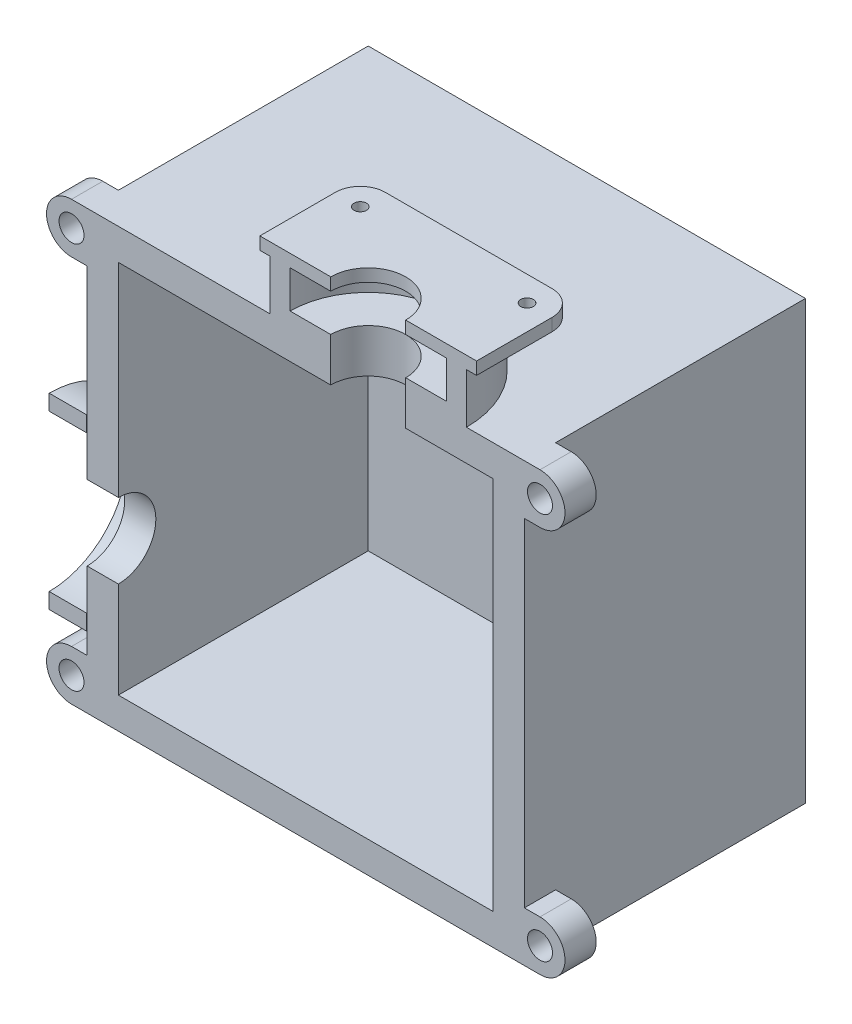
SolidWorks part; units mm, degrees
ref_plane "前视基准面" through (0, 0, 0) normal (0, 0, 1) x (1, 0, 0)
ref_plane "上视基准面" through (0, 0, 0) normal (0, 1, 0) x (1, 0, 0)
ref_plane "右视基准面" through (0, 0, 0) normal (1, 0, 0) x (0, 0, -1)
sketch "草图1" plane through (0, 0, 0) normal (0, 0, 1) x (1, 0, 0)
  line L1 (-45, -45) -> (45, -45)
  line L2 (-45, -45) -> (-45, 45)
  line L3 (-45, 45) -> (45, 45)
  line L4 (45, -45) -> (45, 45)
  line L5 (-45, -45) -> (45, 45) construction
  line L6 (-45, 45) -> (45, -45) construction
  point P0 (0, 0)
  dimension "D1" = 90
extrude "凸台-拉伸2" add sketch "草图1" along normal blind 45
sketch "草图2" plane through (0, 0, 45) normal (0, 0, 1) x (1, 0, 0)
  line L1 (-40, -40) -> (40, -40)
  line L2 (-40, -40) -> (-40, 40)
  line L3 (-40, 40) -> (40, 40)
  line L4 (40, -40) -> (40, 40)
  line L5 (-40, -40) -> (40, 40) construction
  line L6 (-40, 40) -> (40, -40) construction
  point P0 (0, 0)
extrude "切除-拉伸1" cut sketch "草图2" against normal blind 40
sketch "草图3" plane through (0, 45, 0) normal (0, 1, 0) x (1, 0, 0)
  line L0 (45, -45) -> (-45, -45) construction
  line L1 (-15.725, -45) -> (15.725, -45)
  arc A0 (15.725, -45) -> (-15.725, -45) centre (0, -45) ccw
  dimension "D1" = 31.45
extrude "凸台-拉伸3" add sketch "草图3" along normal blind 10
sketch "草图4" plane through (0, 55, 0) normal (0, 1, 0) x (1, 0, 0)
  line L0 (-15.725, -45) -> (15.725, -45) construction
  line L1 (-13.3446, -28.9202) -> (13.3446, -28.9202)
  line L2 (-17.3446, -32.9202) -> (-17.3446, -45)
  line L4 (17.3446, -32.9202) -> (17.3446, -45)
  line L5 (-17.3446, -28.9202) -> (12.4828, -56.5725) construction
  line L6 (-12.4828, -56.5725) -> (17.3446, -28.9202) construction
  line L7 (-17.3446, -45) -> (17.3446, -45)
  line L8 (16.1284, -59.9522) -> (17.3446, -61.0798) construction
  arc A0 (13.3446, -28.9202) -> (17.3446, -32.9202) centre (13.3446, -32.9202) cw
  arc A2 (-13.3446, -28.9202) -> (-17.3446, -32.9202) centre (-13.3446, -32.9202) ccw
  circle A4 centre (13.3446, -32.9202) radius 1
  circle A7 centre (-13.3446, -32.9202) radius 1
  point P0 (0, -45)
  dimension "D2" = 4
extrude "凸台-拉伸4" add sketch "草图4" against normal blind 2 contours L1 A0 L4 L7 L2 A2
sketch "草图5" plane through (0, 55, 0) normal (0, 1, 0) x (1, 0, 0)
  line L0 (-17.3446, -45) -> (17.3446, -45) construction
  circle A0 centre (0, -45) radius 6
extrude "切除-拉伸2" cut sketch "草图5" against normal blind 30
sketch "草图6" plane through (-45, 0, 0) normal (-1, 0, 0) x (0, 0, 1)
  line L1 (45.074, 16.4) -> (45.074, -13.6)
  line L2 (0, 0) -> (61.7305, 0) construction
  arc A0 (45.074, 16.4) -> (45.074, -13.6) centre (45.074, 1.4) ccw
  dimension "D1" = 1.4
extrude "凸台-拉伸5" add sketch "草图6" along normal blind 6
sketch "草图7" plane through (0, 55, 0) normal (0, 1, 0) x (1, 0, 0)
  line L0 (-40, -45) -> (40, -45) construction
  line L1 (-12.5, -45) -> (12.5, -45)
  arc A0 (12.5, -45) -> (-12.5, -45) centre (0, -45) ccw
extrude "切除-拉伸3" cut sketch "草图7" against normal blind 6 from offset 2 offset against normal yes
sketch "草图8" plane through (-51, 0, 0) normal (-1, 0, 0) x (0, 0, 1)
  line L0 (45.074, -13.6) -> (45.074, 16.4) construction
  circle A0 centre (45.074, 1.4) radius 12.5
  dimension "D1" = 25
extrude "切除-拉伸4" cut sketch "草图8" against normal blind 6
sketch "草图9" plane through (-45, 0, 0) normal (-1, 0, 0) x (0, 0, 1)
  line L1 (45, -11.0998) -> (45, 13.8998) construction
  line L2 (0, 0) -> (65.1764, 0) construction
  line L3 (0, 45) -> (0, -45) construction
  circle A0 centre (45, 1.4) radius 6
  dimension "D1" = 1.4
extrude "切除-拉伸5" cut sketch "草图9" against normal blind 6
sketch "草图10" plane through (0, 0, 45) normal (0, 0, 1) x (1, 0, 0)
  line L0 (-47.5, 41) -> (-42.9028, 41) construction
  line L1 (-47.5, 45) -> (-42.9028, 45)
  line L2 (-47.5, 37) -> (-42.9028, 37)
  line L3 (45, 45) -> (15.725, 45) construction
  line L4 (0, 0) -> (0, 63.8347) construction
  line L5 (-66.6212, 0) -> (63.9441, 0) construction
  line L6 (-47.5, -41) -> (-42.9028, -41) construction
  line L7 (-47.5, -45) -> (-42.9028, -45)
  line L8 (-47.5, -37) -> (-42.9028, -37)
  line L9 (-42.9028, 45) -> (-42.9028, 37)
  line L10 (42.4609, 45) -> (42.4609, 37)
  line L11 (-42.9028, -37) -> (-42.9028, -45)
  line L12 (41.0651, -37) -> (41.0651, -45)
  line L13 (41.0651, -37) -> (47.5, -37)
  line L14 (41.0651, -41) -> (47.5, -41) construction
  line L15 (41.0651, -45) -> (47.5, -45)
  line L16 (42.4609, 45) -> (47.5, 45)
  line L17 (42.4609, 41) -> (47.5, 41) construction
  line L18 (42.4609, 37) -> (47.5, 37)
  arc A0 (-47.5, 45) -> (-47.5, 37) centre (-47.5, 41) ccw
  arc A1 (47.5, 37) -> (47.5, 45) centre (47.5, 41) ccw
  arc A2 (-47.5, -45) -> (-47.5, -37) centre (-47.5, -41) cw
  arc A3 (47.5, -37) -> (47.5, -45) centre (47.5, -41) cw
  circle A4 centre (-47.5, 41) radius 2
  circle A5 centre (47.5, 41) radius 2
  circle A6 centre (-47.5, -41) radius 2
  circle A7 centre (47.5, -41) radius 2
  point P2 (0, 41)
  point P16 (0, -41)
  dimension "D1" = 4
  dimension "D3" = 4
  dimension "D4" = 4
  dimension "D5" = 4
  dimension "D6" = 4
  dimension "D2" = 95
extrude "凸台-拉伸6" add sketch "草图10" against normal blind 5
sketch "草图11" plane through (0, 0, 5) normal (0, 0, 1) x (1, 0, 0)
  line L0 (25, 25) -> (25, 60.7622)
  line L3 (-25, -25) -> (25, -25)
  line L4 (25, 25) -> (25, -25)
  line L5 (0, 0) -> (25, -25) construction
  line L6 (-25, -25) -> (25, 25) construction
  line L7 (25, 60.7622) -> (85.8929, 60.7622)
  line L8 (85.8929, 60.7622) -> (85.8929, -73.9397)
  line L9 (85.8929, -73.9397) -> (-86.7109, -73.9397)
  line L10 (-86.7109, -73.9397) -> (-86.7109, -25)
  line L11 (-86.7109, -25) -> (-25, -25)
  point P0 (0, 0)
  dimension "D1" = 50
extrude "切除-拉伸6" cut sketch "草图11" against normal through all both and the other way through all
sketch "草图12" plane through (25, 0, 0) normal (1, 0, 0) x (0, 0, -1)
  line L0 (-45, 40) -> (-45, -25)
  line L1 (-45, -25) -> (-5, -25)
  line L6 (-45, 45) -> (-45, 40)
  line L7 (-45, 40) -> (-5, 40)
  line L8 (-5, 40) -> (-5, -25)
  line L9 (-5, -25) -> (0, -25)
  line L10 (0, -25) -> (0, 45)
  line L11 (0, 45) -> (-45, 45)
  line L12 (-45, 45) -> (-45, 40)
  line L15 (-5, -25) -> (0, -25)
  line L16 (0, -25) -> (0, 45)
  line L17 (0, 45) -> (-45, 45)
  dimension "D1" = 0
extrude "凸台-拉伸8" add sketch "草图12" against normal blind 5
sketch "草图13" plane through (0, 0, 45) normal (0, 0, 1) x (1, 0, 0)
  line L0 (-45, -25) -> (25, -25)
  line L1 (25, -25) -> (25, -20)
  line L2 (25, 45) -> (25, -25) construction
  line L3 (25, -20) -> (-45, -20)
  line L4 (-45, -13.5998) -> (-45, -25) construction
  line L5 (-45, -20) -> (-45, -25)
  dimension "D1" = 5
extrude "凸台-拉伸9" add sketch "草图13" against normal up to next
sketch "草图14" plane through (0, 0, 45) normal (0, 0, 1) x (1, 0, 0)
  line L0 (21.4643, 41) -> (27.5, 41) construction
  line L1 (21.4643, 45) -> (27.5, 45)
  line L2 (21.4643, 37) -> (27.5, 37)
  line L3 (21.4643, -21) -> (27.5, -21) construction
  line L4 (25, 45) -> (25, -25) construction
  line L5 (21.4643, 45) -> (21.4643, 37)
  line L6 (-63.7465, 10) -> (46.0334, 10) construction
  line L7 (-10, 69.0086) -> (-10, -35.2822) construction
  line L8 (-45, 37) -> (-45, 16.3998) construction
  line L9 (-15.725, 45) -> (-47.5, 45) construction
  line L10 (25, -25) -> (-45, -25) construction
  line L11 (21.4643, -25) -> (21.4643, -17)
  line L12 (21.4643, -17) -> (27.5, -17)
  line L13 (21.4643, -25) -> (27.5, -25)
  line L14 (-41.4643, -21) -> (-47.5, -21) construction
  line L15 (-41.4643, -25) -> (-47.5, -25)
  line L16 (-41.4643, -17) -> (-47.5, -17)
  line L17 (-41.4643, -25) -> (-41.4643, -17)
  arc A0 (-122.5, 45) -> (-122.5, 37) centre (-122.5, 41) ccw
  arc A1 (27.5, 37) -> (27.5, 45) centre (27.5, 41) ccw
  circle A2 centre (27.5, 41) radius 2
  circle A3 centre (27.5, -21) radius 2
  arc A4 (27.5, -17) -> (27.5, -25) centre (27.5, -21) cw
  arc A5 (-47.5, -17) -> (-47.5, -25) centre (-47.5, -21) ccw
  circle A6 centre (-47.5, -21) radius 2
  point P2 (-47.5, 41)
  line M7 (-45, -25) -> (25, -25)
  line M8 (25, -25) -> (25, 45)
  line M28 (-45, -13.5998) -> (-45, -25)
  dimension "D1" = 4
  dimension "D2" = 2.5
extrude "凸台-拉伸10" add sketch "草图14" against normal blind 5 contours L2 A1 L1 A2 M8 | L17 L16 M7 M28 | L12 L11 M7 M8 | A4 L12 L13 A3 M8 | L16 A5 L15 A6 M28
